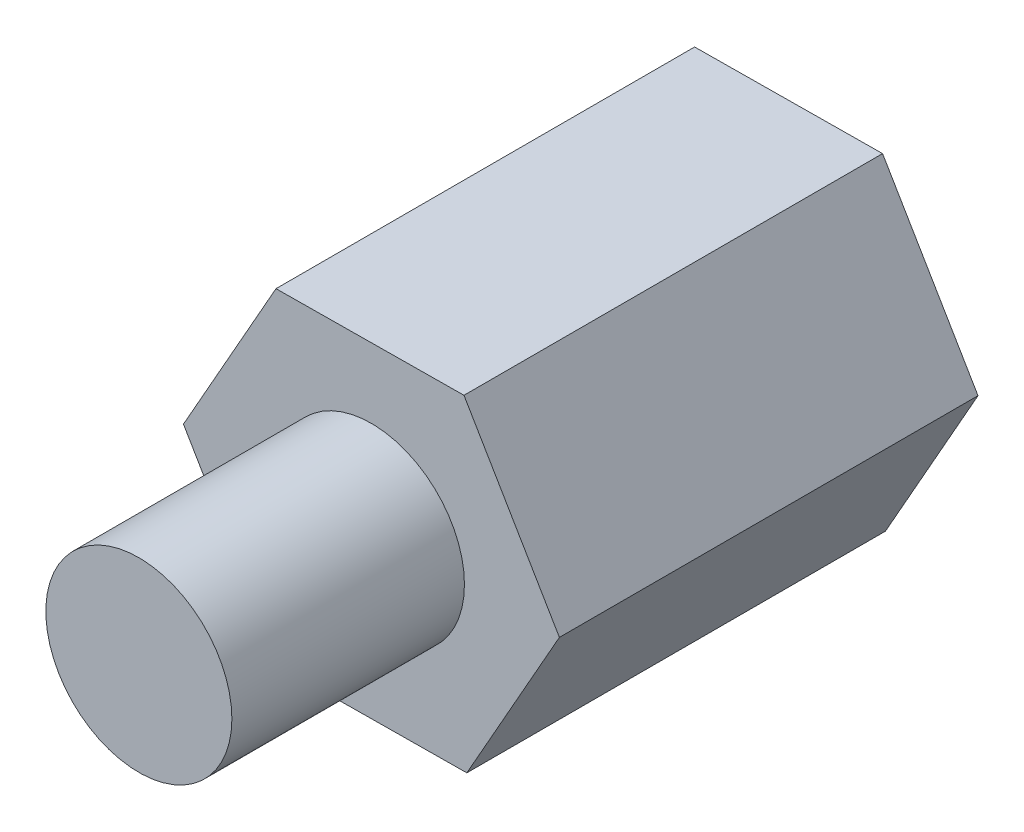
SolidWorks part; units mm, degrees
ref_plane "前视基准面" through (0, 0, 0) normal (0, 0, 1) x (1, 0, 0)
ref_plane "上视基准面" through (0, 0, 0) normal (0, 1, 0) x (1, 0, 0)
ref_plane "右视基准面" through (0, 0, 0) normal (1, 0, 0) x (0, 0, -1)
sketch "草图1" plane through (0, 0, 0) normal (0, 0, 1) x (1, 0, 0)
  line L1 (2.0515, -3.4821) -> (4.0413, 0.0356)
  line L2 (4.0413, 0.0356) -> (1.9898, 3.5177)
  line L3 (1.9898, 3.5177) -> (-2.0515, 3.4821)
  line L4 (-2.0515, 3.4821) -> (-4.0413, -0.0356)
  line L5 (-4.0413, -0.0356) -> (-1.9898, -3.5177)
  line L6 (-1.9898, -3.5177) -> (2.0515, -3.4821)
  circle A0 centre (0, 0) radius 3.5 construction
  circle A1 centre (0, 0) radius 2
extrude "凸台-拉伸1" add sketch "草图1" along normal blind 9
sketch "草图3" plane through (0, 0, 9) normal (0, 0, 1) x (1, 0, 0)
  circle A0 centre (0, 0) radius 2
extrude "凸台-拉伸2" add sketch "草图3" along normal blind 5 separate body
